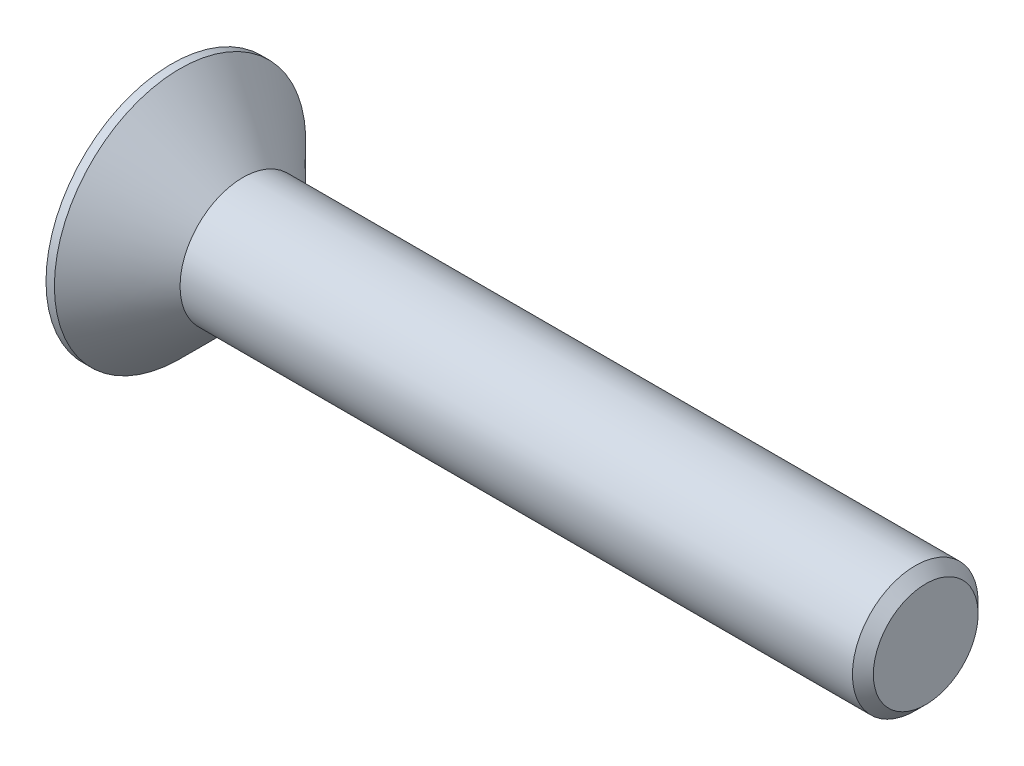
SolidWorks part; units mm, degrees
ref_plane "Front Plane" through (0, 0, 0) normal (0, 0, 1) x (1, 0, 0)
ref_plane "Top Plane" through (0, 0, 0) normal (0, 1, 0) x (1, 0, 0)
ref_plane "Right Plane" through (0, 0, 0) normal (1, 0, 0) x (0, 0, -1)
sketch "Sketch2" plane through (0, 0, 0) normal (0, 0, 1) x (1, 0, 0)
  line L0 (0, 0) -> (0, 3)
  line L1 (0, 3) -> (0.2, 3)
  line L2 (0.2, 3) -> (1.7, 1.5)
  line L3 (1.7, 1.5) -> (17.75, 1.5)
  line L4 (17.75, 1.5) -> (18, 1.25)
  line L5 (18, 1.25) -> (18, 0)
  line L6 (18, 0) -> (0, 0)
  line L7 (-2.2818, 0) -> (8.0811, 0) construction
  dimension "D1" = 6
  dimension "D2" = 0.2
  dimension "D3" = 45
  dimension "D4" = 18
  dimension "D5" = 0.25
  dimension "D6" = 3
revolve "Revolve1" add sketch "Sketch2" angle 360 about L7
sketch "Sketch3" plane through (0, 0, 0) normal (-1, 0, 0) x (0, 0, 1)
  line L1 (0.7217, -1.25) -> (1.4434, 0)
  line L2 (1.4434, 0) -> (0.7217, 1.25)
  line L3 (0.7217, 1.25) -> (-0.7217, 1.25)
  line L4 (-0.7217, 1.25) -> (-1.4434, 0)
  line L5 (-1.4434, 0) -> (-0.7217, -1.25)
  line L6 (-0.7217, -1.25) -> (0.7217, -1.25)
  circle A0 centre (0, 0) radius 1.25 construction
  dimension "D1" = 2.5
extrude "Cut-Extrude1" cut sketch "Sketch3" against normal blind 0.8
